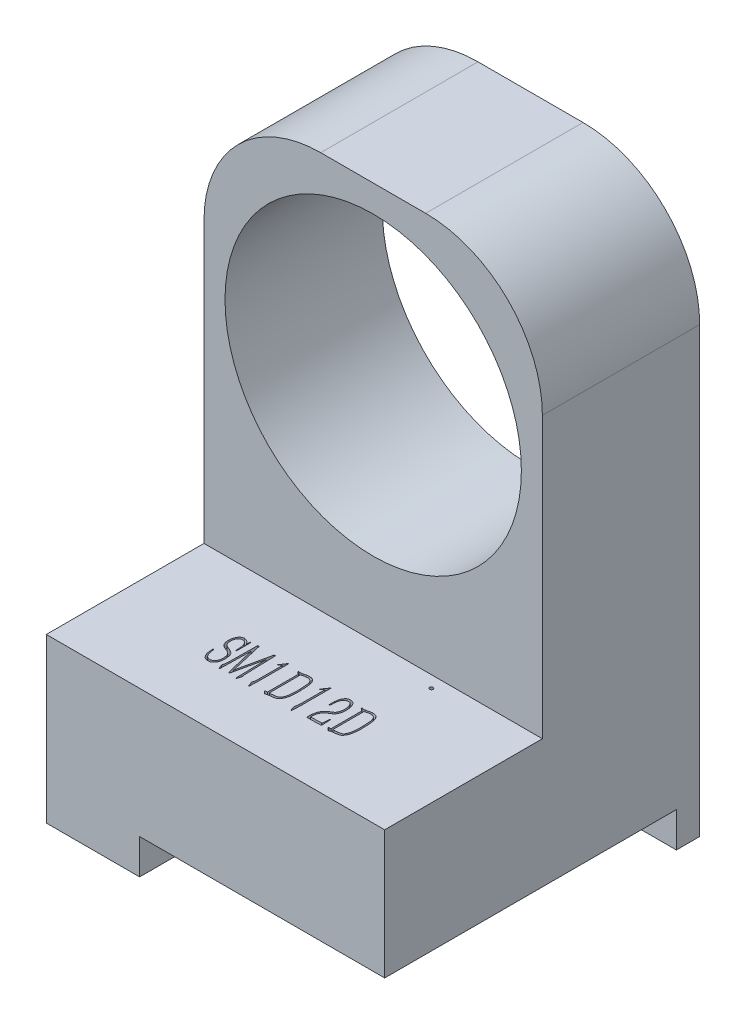
SolidWorks part; units mm, degrees
material "6061 合金"
ref_plane "前视基准面" through (0, 0, 0) normal (0, 0, 1) x (1, 0, 0)
ref_plane "上视基准面" through (0, 0, 0) normal (0, 1, 0) x (1, 0, 0)
ref_plane "右视基准面" through (0, 0, 0) normal (1, 0, 0) x (0, 0, -1)
sketch "草图1" plane through (0, 0, 0) normal (0, 1, 0) x (1, 0, 0)
  line L1 (-14.5, 14.5) -> (14.5, 14.5)
  line L2 (-14.5, 14.5) -> (-14.5, -14.5)
  line L3 (-14.5, -14.5) -> (14.5, -14.5)
  line L4 (14.5, 14.5) -> (14.5, -14.5)
  line L5 (-14.5, 14.5) -> (14.5, -14.5) construction
  line L6 (-14.5, -14.5) -> (14.5, 14.5) construction
  point P0 (0, 0)
  dimension "D1" = 29
  dimension "D2" = 29
extrude "凸台-拉伸1" add sketch "草图1" along normal blind 5
sketch "草图2" plane through (0, 0, 0) normal (0, -1, 0) x (1, 0, 0)
  line L1 (-12.5, 12.5) -> (12.5, 12.5)
  line L2 (-12.5, 12.5) -> (-12.5, -12.5)
  line L3 (-12.5, -12.5) -> (12.5, -12.5)
  line L4 (12.5, 12.5) -> (12.5, -12.5)
  line L5 (-12.5, 12.5) -> (12.5, -12.5) construction
  line L6 (-12.5, -12.5) -> (12.5, 12.5) construction
  point P0 (0, 0)
  dimension "D1" = 25
  dimension "D2" = 25
extrude "切除-拉伸1" cut sketch "草图2" against normal blind 3
sketch "草图3" plane through (0, 5, 0) normal (0, 1, 0) x (1, 0, 0)
  line L0 (0, 0) -> (-6, 0) construction
  line L1 (-16.5, 0) -> (16.5, 0) construction
  line L2 (-6, 0) -> (-6, 7.1924) construction
  dimension "D1" = 6
sketch "草图4" plane through (0, 5, 0) normal (0, 1, 0) x (1, 0, 0)
  line L0 (-14.5, -14.5) -> (14.5, -14.5) construction
  line L1 (-20.5, 14.5) -> (8.5, 14.5)
  line L2 (-20.5, 14.5) -> (-20.5, -14.5)
  line L3 (-20.5, -14.5) -> (8.5, -14.5)
  line L4 (8.5, 14.5) -> (8.5, -14.5)
  line L5 (-20.5, 14.5) -> (8.5, -14.5) construction
  line L6 (-20.5, -14.5) -> (8.5, 14.5) construction
  point P0 (-6, 0)
  dimension "D1" = 29
extrude "凸台-拉伸2" add sketch "草图4" along normal blind 43
sketch "草图6" plane through (0, 3, 0) normal (0, -1, 0) x (1, 0, 0)
  circle A0 centre (0, 0) radius 1.4439
hole_wizard "M4 螺纹孔1" positions "3D草图2" profile "草图7" tap size "M4" standard "GB"
sketch3d "3D草图2"
  point P0 (0, 0, 0)
  point P3 (0, 3, 0)
sketch "草图7" plane through (0, 3, 0) normal (1, 0, 0) x (0, 0, -1)
  line L0 (0, 0) -> (0, 11.0914)
  line L1 (0, 11.0914) -> (1.65, 10.1)
  line L2 (1.65, 10.1) -> (1.65, 0)
  line L5 (1.65, 0) -> (0, 0)
  line L10 (0, 11.0914) -> (-1.65, 10.1) construction
  line L11 (0, -6.35) -> (0, 107.95) construction
  dimension "螺纹孔钻头直径" = 3.3
  dimension "螺纹孔钻头深度" = 10.1
  dimension "导头角度" = 118
cosmetic thread "孔螺蚊线2" parameters "D1"=8, "D2"=4
sketch "草图8" plane through (0, 0, 14.5) normal (0, 0, 1) x (1, 0, 0)
  line L0 (-6, 48) -> (-6, 33) construction
  line L1 (-20.5, 48) -> (8.5, 48) construction
  line L2 (12.5, 3) -> (-12.5, 3) construction
  dimension "D1" = 30
hole_wizard "M27 螺纹孔1" positions "3D草图3" profile "草图9" tap size "M27" standard "GB" end condition through all
sketch3d "3D草图3"
  point P0 (-6, 33, 14.5)
sketch "草图9" plane through (-6, 33, 14.5) normal (1, 0, 0) x (0, -1, 0)
  line L0 (0, 0) -> (0, 29)
  line L1 (0, 29) -> (12.7, 29)
  line L2 (12.7, 29) -> (12.7, 0)
  line L5 (12.7, 0) -> (0, 0)
  line L11 (0, -6.35) -> (0, 107.95) construction
  dimension "通孔螺纹孔钻头直径" = 25.4
  dimension "通孔螺纹孔钻头深度" = 29
cosmetic thread "孔螺蚊线3" parameters "D2"=27
sketch "草图10" plane through (0, 0, 14.5) normal (0, 0, 1) x (1, 0, 0)
  circle A0 centre (-6, 33) radius 18
extrude "切除-拉伸2" cut sketch "草图10" against normal up to surface (15.516 mm away)
sketch "草图11" plane through (0, 0, 0) normal (0, -1, 0) x (-1, 0, 0)
  circle A0 centre (12.5, 12.5) radius 1
extrude "切除-拉伸3" cut sketch "草图11" against normal up to surface (3 mm away) up to face at (0, 3, -1.65)
sketch "草图12" plane through (0, 0, 14.5) normal (0, 0, 1) x (1, 0, 0)
  line L2 (-20.5, 48) -> (-20.5, 43.6654)
  line L3 (-15.9499, 48) -> (-20.5, 48)
  line L4 (-20.5, 48) -> (-20.5, 43.6654)
  line L5 (-15.9499, 48) -> (-20.5, 48)
  line L6 (8.5, 48) -> (3.9499, 48)
  line L7 (8.5, 43.6654) -> (8.5, 48)
  line L8 (8.5, 48) -> (3.9499, 48)
  line L9 (8.5, 43.6654) -> (8.5, 48)
  arc A1 (-15.9499, 48) -> (-20.5, 43.6654) centre (-6, 33) ccw
  arc A2 (-15.9499, 48) -> (-20.5, 43.6654) centre (-6, 33) ccw
  arc A3 (8.5, 43.6654) -> (3.9499, 48) centre (-6, 33) ccw
  arc A4 (8.5, 43.6654) -> (3.9499, 48) centre (-6, 33) ccw
  dimension "D1" = 0
  dimension "D2" = 0
extrude "切除-拉伸4" cut sketch "草图12" against normal up to surface (15.516 mm away) up to face at (-6, 45.7, -1.016)
sketch "草图13" plane through (-14.5, 0, 0) normal (-1, 0, 0) x (0, 0, 1)
  line L4 (-14.5, 0) -> (14.5, 0)
  line L5 (14.5, 0) -> (14.5, 5)
  line L6 (14.5, 5) -> (-14.5, 5)
  line L7 (-14.5, 5) -> (-14.5, 0)
  line L8 (-14.5, 0) -> (14.5, 0)
  line L9 (14.5, 0) -> (14.5, 5)
  line L10 (14.5, 5) -> (-14.5, 5)
  line L11 (-14.5, 5) -> (-14.5, 0)
  dimension "D1" = 0
extrude "凸台-拉伸3" add sketch "草图13" along normal up to surface (6 mm away) up to face at (-20.5, 25.1115, -0.3387)
sketch "草图14" plane through (0, 5, 0) normal (0, 1, 0) x (1, 0, 0)
  line L4 (8.5, 14.5) -> (8.5, -14.5)
  line L5 (8.5, -14.5) -> (14.5, -14.5)
  line L6 (14.5, -14.5) -> (14.5, 14.5)
  line L7 (14.5, 14.5) -> (8.5, 14.5)
  line L8 (8.5, 14.5) -> (8.5, -14.5)
  line L9 (8.5, -14.5) -> (14.5, -14.5)
  line L10 (14.5, -14.5) -> (14.5, 14.5)
  line L11 (14.5, 14.5) -> (8.5, 14.5)
  dimension "D1" = 0
extrude "切除-拉伸5" cut sketch "草图14" against normal through all
sketch "草图15" plane through (0, 0, 0) normal (0, -1, 0) x (1, 0, 0)
  line L1 (8.5, 12.5) -> (-20.5, 12.5)
  line L2 (8.5, 12.5) -> (8.5, 14.5)
  line L3 (8.5, 14.5) -> (-20.5, 14.5)
  line L4 (-20.5, 12.5) -> (-20.5, 14.5)
extrude "切除-拉伸6" cut sketch "草图15" against normal through all
fillet "圆角1" radius 10 2 edges at (8.5, 48, -7.758) (-20.5, 48, -7.758)
sketch "草图16" plane through (0, 0, 12.5) normal (0, 0, 1) x (1, 0, 0)
  line L0 (-20.5, 22.3346) -> (-20.5, 14)
  line L1 (-20.5, 22.3346) -> (-20.5, 0) construction
  line L2 (-20.5, 14) -> (8.5, 14)
  line L3 (8.5, 22.3346) -> (8.5, 3) construction
  line L4 (8.5, 14) -> (8.5, 22.3346)
  line L5 (-20.5, 0) -> (-12.5, 0) construction
  arc A0 (-20.5, 22.3346) -> (8.5, 22.3346) centre (-6, 33) ccw construction
  arc A1 (-20.5, 22.3346) -> (8.5, 22.3346) centre (-6, 33) ccw
  dimension "D1" = 14
extrude "切除-拉伸7" cut sketch "草图16" against normal up to surface (13.516 mm away) up to face at (-6, 45.7, -1.016)
sketch "草图17" plane through (0, 14, 0) normal (0, 1, 0) x (1, 0, 0)
  text T0 "SM1D12D"
extrude "切除-拉伸8" cut sketch "草图17" against normal blind 0.5
